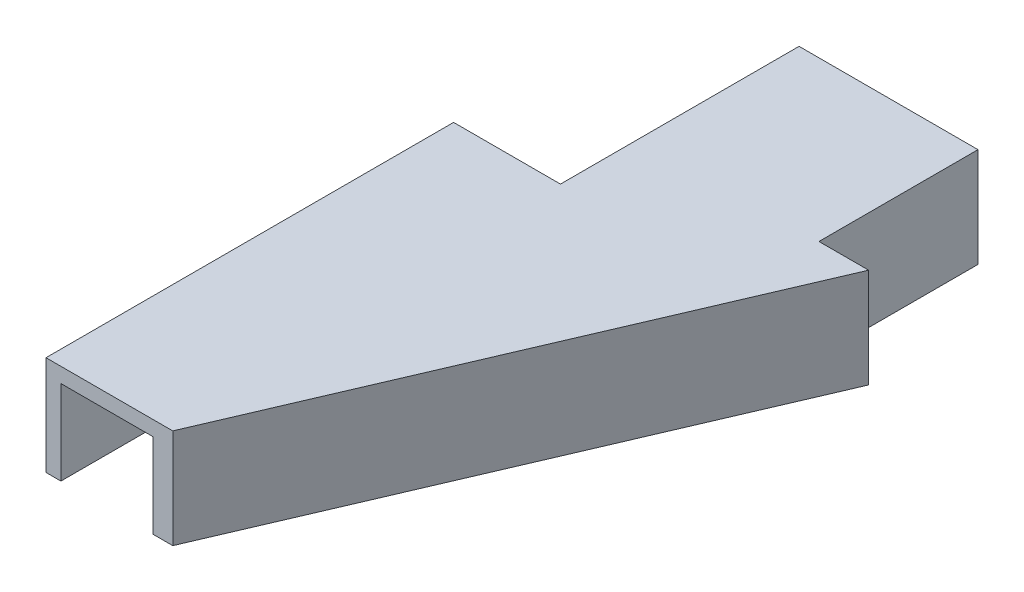
SolidWorks part; units mm, degrees
ref_plane "Plan de face" through (0, 0, 0) normal (0, 0, 1) x (1, 0, 0)
ref_plane "Plan de dessus" through (0, 0, 0) normal (0, 1, 0) x (1, 0, 0)
ref_plane "Plan de droite" through (0, 0, 0) normal (1, 0, 0) x (0, 0, -1)
sketch "Esquisse1" plane through (0, 0, 0) normal (0, 1, 0) x (1, 0, 0)
  line L0 (0, 0) -> (0, 130)
  line L1 (0, 130) -> (36, 130)
  line L2 (36, 130) -> (36, 98)
  line L3 (36, 98) -> (46, 98)
  line L5 (0, 0) -> (4, 0)
  line L6 (4, 0) -> (46, 98)
  dimension "D1" = 130
  dimension "D2" = 32
  dimension "D3" = 36
extrude "Boss.-Extru.1" add sketch "Esquisse1" along normal blind 20
sketch "Esquisse3" plane through (0, 0, 0) normal (0, 0, 1) x (1, 0, 0)
  line L0 (0, 20) -> (-21.5, 20)
  line L1 (-21.5, 20) -> (-21.5, 0)
  line L2 (-21.5, 0) -> (-18.5, 0)
  line L3 (-18.5, 0) -> (-18.5, 17)
  line L4 (-18.5, 17) -> (0, 17)
  line L5 (0, 20) -> (0, 0) construction
  line L6 (0, 20) -> (0, 17)
  dimension "D1" = 3
  dimension "D2" = 18.5
  dimension "D3" = 3
extrude "Boss.-Extru.2" add sketch "Esquisse3" against normal blind 85 contours L3 L4 L6 L0 L1 L2
sketch "Esquisse4" plane through (0, 0, 0) normal (-1, 0, 0) x (0, 0, 1)
  line L1 (-130, 20) -> (-80, 20)
  line L2 (-130, 20) -> (-130, 0)
  line L3 (-130, 0) -> (-80, 0)
  line L4 (-80, 20) -> (-80, 0)
  line L5 (-130, 20) -> (-80, 0) construction
  line L6 (-130, 0) -> (-80, 20) construction
  line L7 (-85, 0) -> (0, 0) construction
  point P4 (-105, 10)
  dimension "D1" = 20
  dimension "D2" = 50
extrude "Enlèv. mat.-Extru.1" cut sketch "Esquisse4" along normal blind 47
sketch "Esquisse5" plane through (0, 0, 0) normal (0, -1, 0) x (1, 0, 0)
  line L12 (5, -15.0263) -> (5, -125)
  line L13 (5, -125) -> (31, -125)
  line L14 (31, -125) -> (31, -93)
  line L15 (31, -93) -> (38.4173, -93)
  line L16 (38.4173, -93) -> (5, -15.0263)
  line L17 (5, -15.0263) -> (5, -125)
  line L18 (5, -125) -> (31, -125)
  line L19 (31, -125) -> (31, -93)
  line L20 (31, -93) -> (38.4173, -93)
  line L21 (38.4173, -93) -> (5, -15.0263)
  dimension "D1" = 5
extrude "Enlèv. mat.-Extru.2" cut sketch "Esquisse5" against normal up to vertex (17 mm away)
sketch "Esquisse6" plane through (0, 0, -80) normal (0, 0, -1) x (-1, 0, 0)
  line L1 (21.5, 0) -> (0, 0)
  line L2 (21.5, 0) -> (21.5, 20)
  line L3 (21.5, 20) -> (0, 20)
  line L4 (0, 0) -> (0, 20)
  line L5 (21.5, 0) -> (0, 20) construction
  line L6 (21.5, 20) -> (0, 0) construction
  point P4 (10.75, 10)
  dimension "D1" = 20
  dimension "D2" = 21.5
extrude "Boss.-Extru.3" add sketch "Esquisse6" along normal blind 2
